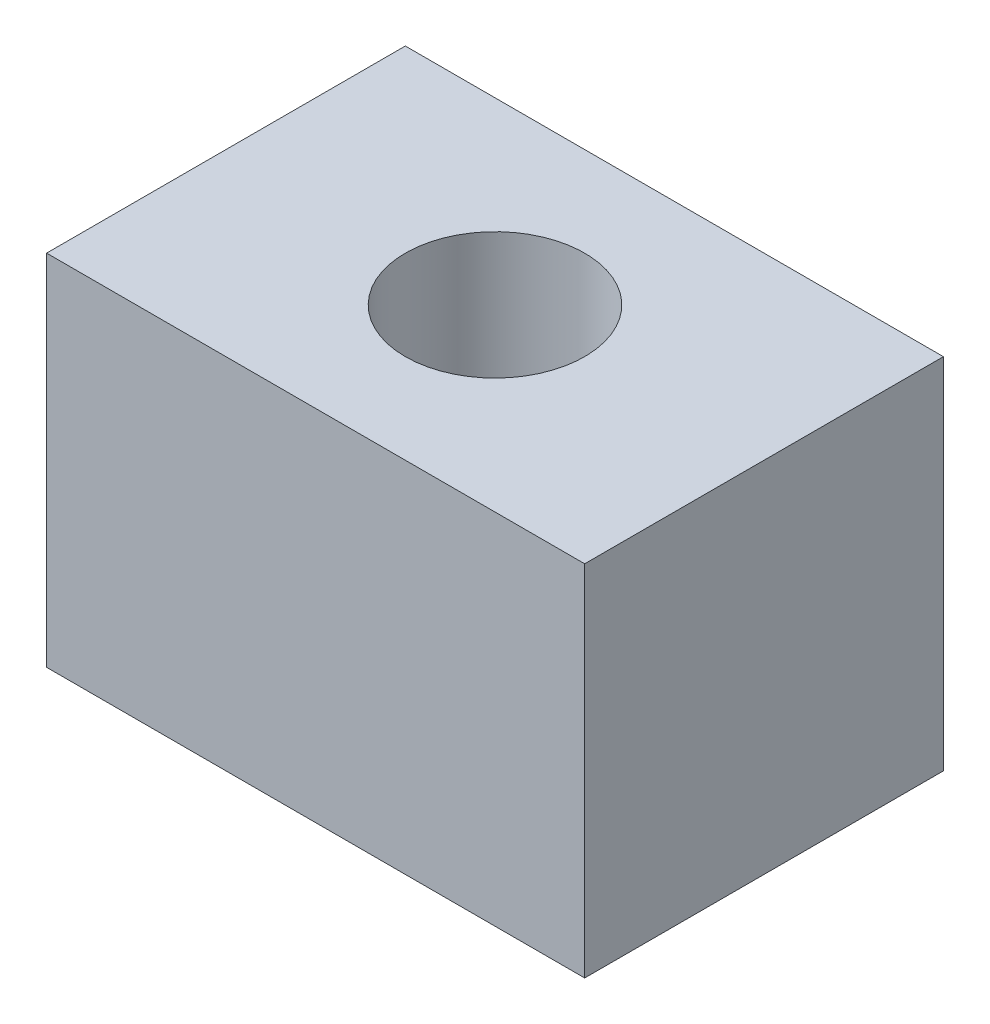
SolidWorks part; units mm, degrees
ref_plane "Plan de face" through (0, 0, 0) normal (0, 0, 1) x (1, 0, 0)
ref_plane "Plan de dessus" through (0, 0, 0) normal (0, 1, 0) x (1, 0, 0)
ref_plane "Plan de droite" through (0, 0, 0) normal (1, 0, 0) x (0, 0, -1)
sketch "Esquisse1" plane through (0, 0, 0) normal (0, 1, 0) x (1, 0, 0)
  line L1 (-4.5, -3) -> (4.5, -3)
  line L2 (-4.5, -3) -> (-4.5, 3)
  line L3 (-4.5, 3) -> (4.5, 3)
  line L4 (4.5, -3) -> (4.5, 3)
  line L5 (-4.5, -3) -> (4.5, 3) construction
  line L6 (-4.5, 3) -> (4.5, -3) construction
  circle A0 centre (0, 0) radius 1.5
  point P0 (0, 0)
  dimension "D3" = 3
  dimension "D1" = 9
  dimension "D2" = 6
extrude "Boss.-Extru.1" add sketch "Esquisse1" along normal blind 6
